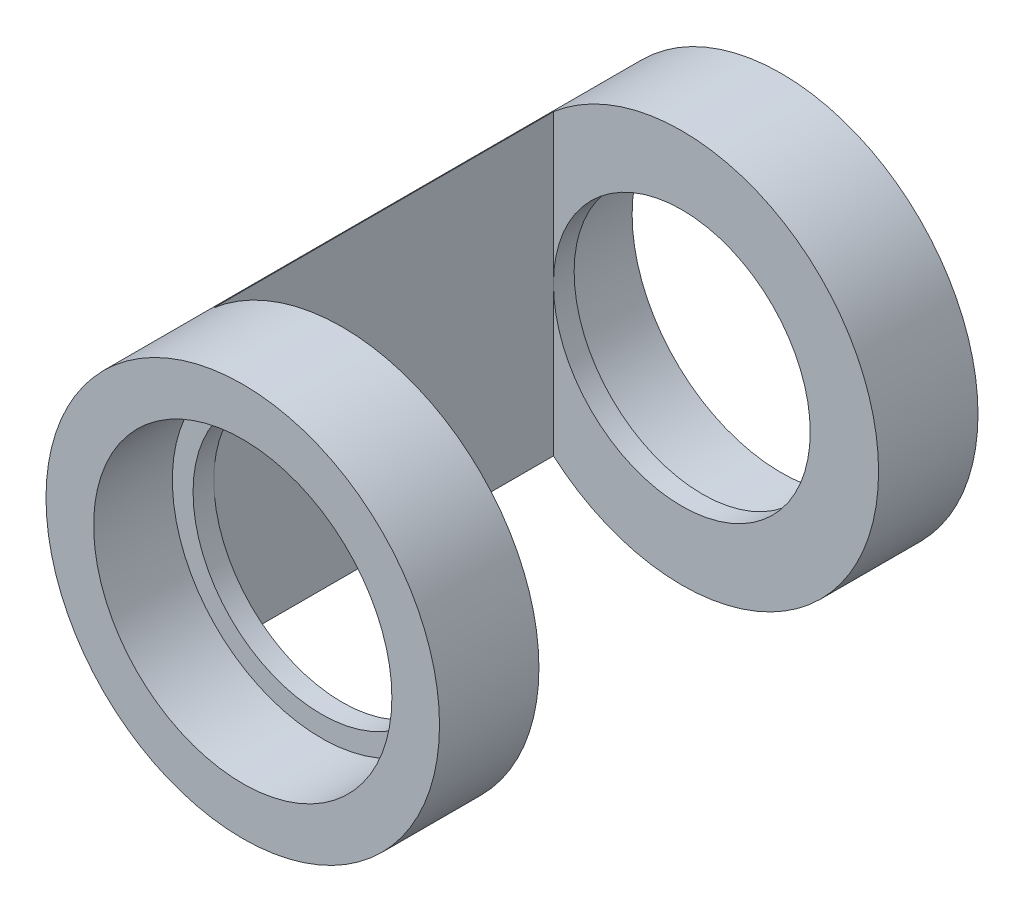
SolidWorks part; units mm, degrees
ref_plane "前视基准面" through (0, 0, 0) normal (0, 0, 1) x (1, 0, 0)
ref_plane "上视基准面" through (0, 0, 0) normal (0, 1, 0) x (1, 0, 0)
ref_plane "右视基准面" through (0, 0, 0) normal (1, 0, 0) x (0, 0, -1)
sketch "草图1" plane through (0, 0, 0) normal (0, 0, 1) x (1, 0, 0)
  circle A0 centre (0, 0) radius 47.5
  dimension "D1" = 95
extrude "拉伸1" add sketch "草图1" along normal blind 130
sketch "草图2" plane through (0, 0, 130) normal (0, 0, 1) x (1, 0, 0)
  circle A0 centre (0, 0) radius 36
extrude "切除-拉伸1" cut sketch "草图2" against normal blind 19
sketch "草图3" plane through (0, 0, 0) normal (0, 0, -1) x (-1, 0, 0)
  circle A0 centre (0, 0) radius 36
extrude "切除-拉伸2" cut sketch "草图3" against normal blind 19
sketch "草图4" plane through (0, 0, 19) normal (0, 0, -1) x (-1, 0, 0)
  circle A0 centre (0, 0) radius 31
  dimension "D1" = 62
extrude "切除-拉伸3" cut sketch "草图4" against normal blind 139
ref_plane "基准面1" through (0, 0, 24) normal (0, 0, -1) x (-1, 0, 0)
sketch "草图5" plane through (0, 0, 24) normal (0, 0, -1) x (-1, 0, 0)
  line L1 (31, -35.9896) -> (31, 35.9896)
  arc A1 (31, 35.9896) -> (31, -35.9896) centre (0, 0) ccw
extrude "切除-拉伸4" cut sketch "草图5" against normal blind 82
